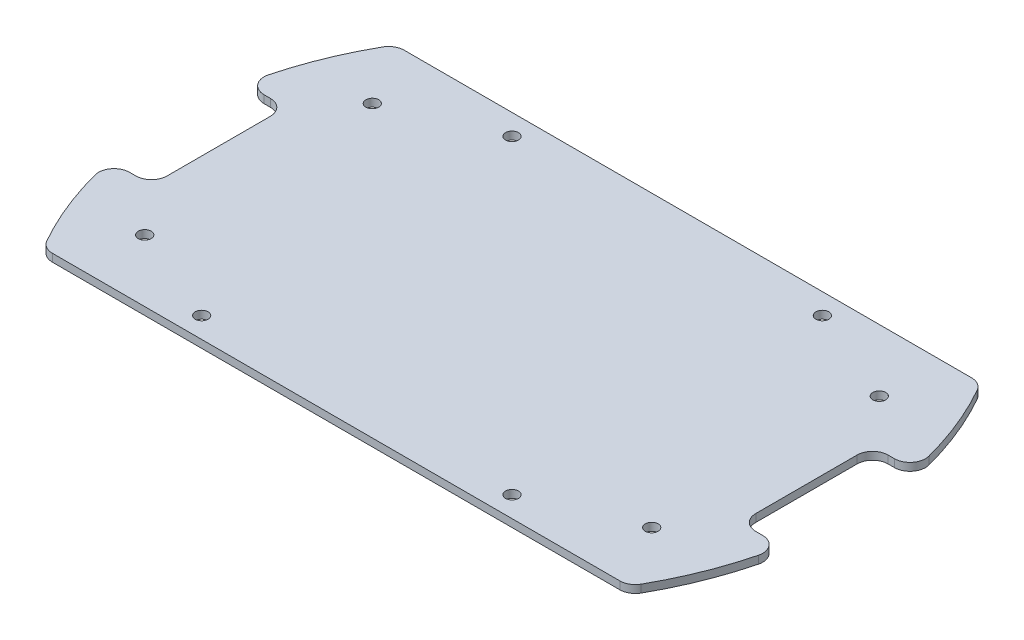
SolidWorks part; units mm, degrees
ref_plane "前基準面" through (0, 0, 0) normal (0, 0, 1) x (1, 0, 0)
ref_plane "上基準面" through (0, 0, 0) normal (0, 1, 0) x (1, 0, 0)
ref_plane "右基準面" through (0, 0, 0) normal (1, 0, 0) x (0, 0, -1)
sketch "草圖7" plane through (0, 0, 0) normal (0, 1, 0) x (1, 0, 0)
  line L1 (-34, 34) -> (34, 34)
  line L2 (-34, 34) -> (-34, -34)
  line L3 (-34, -34) -> (34, -34)
  line L4 (34, 34) -> (34, -34)
  line L5 (-34, 34) -> (34, -34) construction
  line L6 (-34, -34) -> (34, 34) construction
  point P0 (0, 0)
  point P7 (-30, 30)
  point P10 (30, 30)
  point P11 (30, -30)
  point P12 (-30, -30)
  point P13 (0, 0)
  dimension "D1" = 68
  dimension "D2" = 4
  dimension "D3" = 4
sketch "草圖10" plane through (0, 0, 0) normal (0, 1, 0) x (1, 0, 0)
  line L0 (-56.5685, 34) -> (56.5685, 34)
  line L1 (-34, 34) -> (34, 34) construction
  line L2 (-56.5685, -34) -> (56.5685, -34)
  line L3 (-34, -34) -> (34, -34) construction
  line L4 (-34, 34) -> (-34, -34) construction
  line L5 (0, 0) -> (0, 19.0172) construction
  line L6 (0, 0) -> (-12.2861, 0) construction
  line L7 (-56.707, 13) -> (-56.707, -13)
  line L8 (-64.707, 13) -> (64.707, 13)
  line L9 (56.707, 13) -> (56.707, -13)
  line L10 (-64.707, -13) -> (64.7924, -12.5675)
  arc A0 (-64.707, -13) -> (-56.5685, -34) centre (0, 0) ccw
  arc A3 (-56.5685, 34) -> (-64.707, 13) centre (0, 0) ccw
  arc A4 (64.707, 13) -> (56.5685, 34) centre (0, 0) ccw
  arc A5 (56.5685, -34) -> (64.7924, -12.5675) centre (0, 0) ccw
  point P12 (-49, 22)
  point P24 (56.707, 0)
  point P27 (-56.707, 0)
  dimension "D1" = 8
  dimension "D2" = 13
  dimension "D4" = 15
  dimension "D5" = 12
extrude "填料-伸長2" add sketch "草圖10" along normal blind 1.5
hole_wizard "M3x0.5  螺絲攻的螺孔鑽1" positions "3D草圖2" profile "草圖13" hole size "M3x0.5" standard "JIS"
sketch3d "3D草圖2"
  point P0 (-30, 0, -30)
  point P3 (-30, 1.5, -30)
  point P5 (-30, 1.5, 30)
  point P11 (30, 1.5, -30)
  point P13 (30, 1.5, 30)
sketch "草圖13" plane through (30, 1.5, 30) normal (1, 0, 0) x (0, 0, 1)
  line L0 (0, 0) -> (0, 4.7511)
  line L1 (0, 4.7511) -> (1.25, 4)
  line L2 (1.25, 4) -> (1.25, 0)
  line L5 (1.25, 0) -> (0, 0)
  line L10 (0, 4.7511) -> (-1.25, 4) construction
  line L11 (0, -6.35) -> (0, 107.95) construction
  dimension "鑽孔直徑" = 2.5
  dimension "鑽孔深度" = 4
  dimension "導頭角度" = 118
hole_wizard "M3x0.5  螺絲攻的螺孔鑽2" positions "3D草圖3" profile "草圖14" hole size "M3x0.5" standard "JIS"
sketch3d "3D草圖3"
  point P0 (-49, 1.5, -22)
sketch "草圖14" plane through (-49, 1.5, -22) normal (1, 0, 0) x (0, 0, 1)
  line L0 (0, 0) -> (0, 4.7511)
  line L1 (0, 4.7511) -> (1.25, 4)
  line L2 (1.25, 4) -> (1.25, 0)
  line L5 (1.25, 0) -> (0, 0)
  line L10 (0, 4.7511) -> (-1.25, 4) construction
  line L11 (0, -6.35) -> (0, 107.95) construction
  dimension "鑽孔直徑" = 2.5
  dimension "鑽孔深度" = 4
  dimension "導頭角度" = 118
pattern_linear "直線複製排列1" count 2 spacing 98 along (1, 0, 0) count 2 spacing 44 along (0, 0, 1) of "M3x0.5  螺絲攻的螺孔鑽2"
fillet "圓角1" radius 3 12 edges at (56.5685, 0.75, -34) (64.707, 0.75, -13) (56.707, 0.75, -13) (56.707, 0.75, 12.5945) (64.7924, 0.75, 12.5675) (56.5685, 0.75, 34) (-56.5685, 0.75, 34) (-64.707, 0.75, 13) (-56.707, 0.75, 12.9733) (-56.707, 0.75, -13) (-56.5685, 0.75, -34) (-64.707, 0.75, -13)
